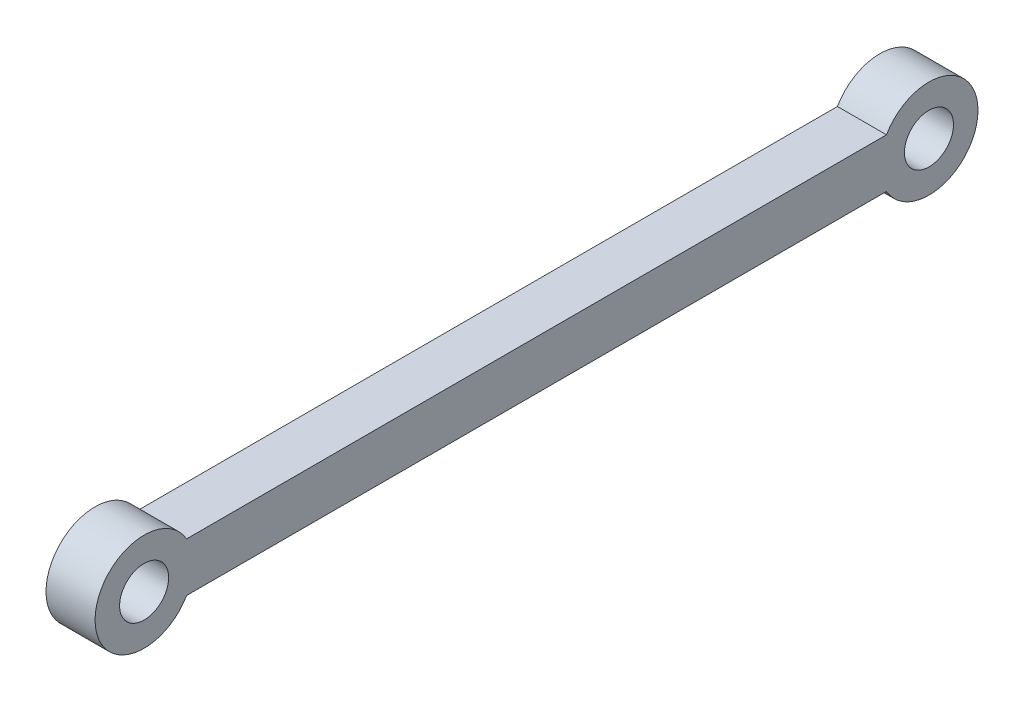
SolidWorks part; units mm, degrees
ref_plane "정면" through (0, 0, 0) normal (0, 0, 1) x (1, 0, 0)
ref_plane "윗면" through (0, 0, 0) normal (0, 1, 0) x (1, 0, 0)
ref_plane "우측면" through (0, 0, 0) normal (1, 0, 0) x (0, 0, -1)
sketch "스케치1" plane through (0, 0, 0) normal (1, 0, 0) x (0, 0, -1)
  line L0 (-20, 0) -> (20, 0) construction
  line L1 (-17.8349, 1.25) -> (17.8349, 1.25)
  line L3 (-17.8349, -1.25) -> (17.8349, -1.25)
  line L5 (0, 1.25) -> (0, -1.25) construction
  arc A0 (-17.8349, 1.25) -> (-17.8349, -1.25) centre (-20, 0) ccw
  circle A1 centre (-20, 0) radius 1.25
  arc A2 (17.8349, -1.25) -> (17.8349, 1.25) centre (20, 0) ccw
  circle A3 centre (20, 0) radius 1.25
  dimension "D3" = 5
  dimension "D4" = 5
  dimension "D1" = 2.5
  dimension "D2" = 40
extrude "보스-돌출1" add sketch "스케치1" along normal blind 2.5
equation "\"link11\" = 80"
equation "\"link12\" = 40"
equation "\"link21\"= 60"
equation "\"link22\"= 40"
equation "\"link31\"= 50"
equation "\"link32\"= 40"
equation "\"link41\"= 40"
equation "\"link42\"= 40"
equation "\"D2@스케치1\"=\"link41\""
